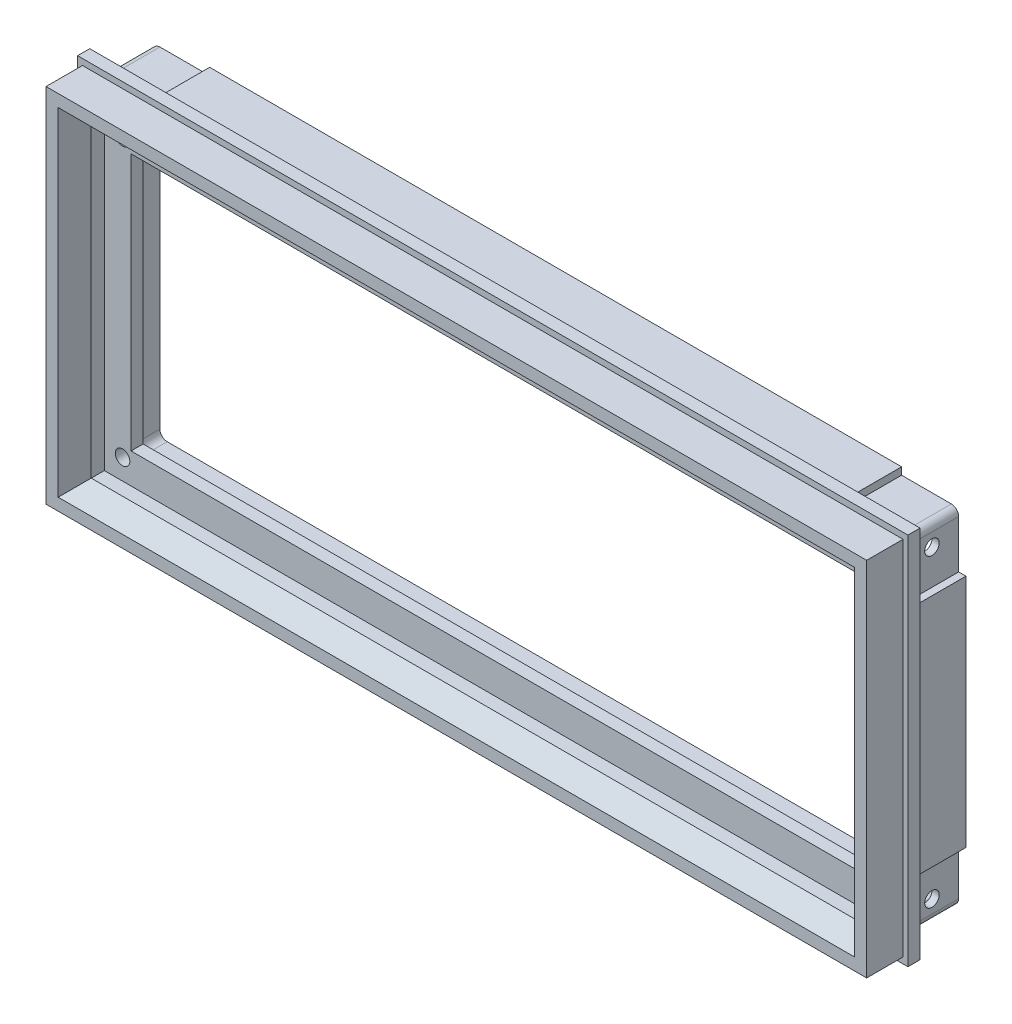
SolidWorks part; units mm, degrees
ref_plane "Plan de face" through (0, 0, 0) normal (0, 0, 1) x (1, 0, 0)
ref_plane "Plan de dessus" through (0, 0, 0) normal (0, 1, 0) x (1, 0, 0)
ref_plane "Plan de droite" through (0, 0, 0) normal (1, 0, 0) x (0, 0, -1)
sketch "Esquisse1" plane through (0, 0, 0) normal (0, 0, 1) x (1, 0, 0)
  line L1 (0, 0) -> (171, 0)
  line L2 (0, 0) -> (0, -77)
  line L3 (0, -77) -> (171, -77)
  line L4 (171, 0) -> (171, -77)
  line L5 (11, -12) -> (160, -12)
  line L6 (11, -12) -> (11, -65)
  line L7 (11, -65) -> (160, -65)
  line L8 (160, -12) -> (160, -65)
  line L9 (9.25, -10) -> (161.75, -10) construction
  line L10 (9.25, -10) -> (9.25, -67) construction
  line L11 (9.25, -67) -> (161.75, -67) construction
  line L12 (161.75, -10) -> (161.75, -67) construction
  circle A0 centre (9.25, -10) radius 1.5
  circle A1 centre (161.75, -10) radius 1.5
  circle A2 centre (161.75, -67) radius 1.5
  circle A3 centre (9.25, -67) radius 1.5
  point P9 (160, -38.5)
  point P10 (171, -38.5)
  point P11 (85.5, 0)
  point P12 (85.5, -12)
  point P21 (9.25, -38.5)
  point P22 (0, -38.5)
  point P23 (85.5, -67)
  point P24 (85.5, -77)
  dimension "D4" = 3
  dimension "D5" = 3
  dimension "D6" = 3
  dimension "D7" = 3
  dimension "D1" = 171
  dimension "D2" = 77
  dimension "D3" = 53
  dimension "D8" = 152.5
  dimension "D9" = 57
  dimension "D10" = 149
extrude "Boss.-Extru.1" add sketch "Esquisse1" along normal blind 2.5
sketch "Esquisse2" plane through (0, 0, 2.5) normal (0, 0, 1) x (1, 0, 0)
  line L0 (0, 0) -> (0, -77) construction
  line L1 (1, -1.25) -> (170, -1.25)
  line L2 (1, -1.25) -> (1, -75.75)
  line L3 (1, -75.75) -> (170, -75.75)
  line L4 (170, -1.25) -> (170, -75.75)
  line L5 (171, 0) -> (0, 0) construction
  line L7 (5.5, -5.75) -> (165.5, -5.75)
  line L8 (5.5, -5.75) -> (5.5, -71.25)
  line L9 (5.5, -71.25) -> (165.5, -71.25)
  line L10 (165.5, -5.75) -> (165.5, -71.25)
  point P6 (1, -38.5)
  point P7 (0, -38.5)
  point P10 (85.5, 0)
  point P11 (85.5, -1.25)
  dimension "D1" = 74.5
  dimension "D2" = 4.5
  dimension "D3" = 4.5
  dimension "D4" = 4.5
  dimension "D5" = 4.5
  dimension "D6" = 169
  dimension "D7" = 65.5
  dimension "D8" = 160
extrude "Boss.-Extru.2" add sketch "Esquisse2" along normal blind 7.5
chamfer "Chanfrein7" distance 2 angle 67.39 4 edges at (85.5, -71.25, 10) (165.5, -38.5, 10) (85.5, -5.75, 10) (5.5, -38.5, 10)
sketch "Esquisse4" plane through (0, 0, 0) normal (0, 0, -1) x (-1, 0, 0)
  line L0 (-171, 0) -> (0, 0) construction
  line L1 (-165.5, -4.425) -> (-5.5, -4.425)
  line L2 (-167, -5.925) -> (-167, -71.075)
  line L3 (-165.5, -72.575) -> (-5.5, -72.575)
  line L4 (-4, -5.925) -> (-4, -71.075)
  line L5 (-167, -2.925) -> (-4, -2.925)
  line L6 (-168.5, -4.425) -> (-168.5, -72.575)
  line L7 (-167, -74.075) -> (-4, -74.075)
  line L8 (-2.5, -4.425) -> (-2.5, -72.575)
  line L9 (-170, -1.425) -> (-1, -1.425) construction
  line L10 (-170, -1.425) -> (-170, -75.575) construction
  line L11 (-170, -75.575) -> (-1, -75.575) construction
  line L12 (-1, -1.425) -> (-1, -75.575) construction
  line L14 (-171, -77) -> (-171, 0) construction
  line L16 (-156.75, -75.575) -> (-14.25, -75.575)
  line L17 (-156.75, -75.575) -> (-156.75, -74.075)
  line L18 (-156.75, -74.075) -> (-14.25, -74.075)
  line L19 (-14.25, -75.575) -> (-14.25, -74.075)
  line L20 (-14.25, -2.925) -> (-156.75, -2.925)
  line L21 (-14.25, -2.925) -> (-14.25, -1.425)
  line L22 (-14.25, -1.425) -> (-156.75, -1.425)
  line L23 (-156.75, -2.925) -> (-156.75, -1.425)
  line L24 (-170, -14.3) -> (-168.5, -14.3)
  line L25 (-170, -14.3) -> (-170, -62.7)
  line L26 (-170, -62.7) -> (-168.5, -62.7)
  line L27 (-168.5, -14.3) -> (-168.5, -62.7)
  line L28 (-2.5, -62.7) -> (-1, -62.7)
  line L29 (-2.5, -62.7) -> (-2.5, -14.3)
  line L30 (-2.5, -14.3) -> (-1, -14.3)
  line L31 (-1, -62.7) -> (-1, -14.3)
  arc A0 (-4, -5.925) -> (-5.5, -4.425) centre (-5.5, -5.925) ccw
  arc A1 (-4, -2.925) -> (-2.5, -4.425) centre (-4, -4.425) cw
  arc A2 (-2.5, -72.575) -> (-4, -74.075) centre (-4, -72.575) cw
  arc A3 (-4, -71.075) -> (-5.5, -72.575) centre (-5.5, -71.075) cw
  arc A4 (-168.5, -72.575) -> (-167, -74.075) centre (-167, -72.575) ccw
  arc A5 (-167, -71.075) -> (-165.5, -72.575) centre (-165.5, -71.075) ccw
  arc A6 (-167, -2.925) -> (-168.5, -4.425) centre (-167, -4.425) ccw
  arc A7 (-167, -5.925) -> (-165.5, -4.425) centre (-165.5, -5.925) cw
  point P14 (-85.5, 0)
  point P15 (-85.5, -1.425)
  point P18 (-171, -38.5)
  point P19 (-170, -38.5)
  point P28 (-85.5, -2.925)
  point P29 (-85.5, -1.425)
  point P30 (-85.5, -75.575)
  point P31 (-85.5, -74.075)
  point P40 (-170, -38.5)
  point P41 (-168.5, -38.5)
  dimension "D14" = 1.5
  dimension "D1" = 1.5
  dimension "D2" = 1.5
  dimension "D3" = 1.5
  dimension "D4" = 1.5
  dimension "D5" = 3
  dimension "D6" = 3
  dimension "D7" = 3
  dimension "D8" = 3
  dimension "D9" = 74.15
  dimension "D10" = 169
  dimension "D11" = 142.5
  dimension "D12" = 142.5
  dimension "D13" = 48.4
extrude "Boss.-Extru.3" add sketch "Esquisse4" along normal blind 10.45 contours L5 A6 L6 A4 L7 A2 L8 A1 L2 A7 L1 A0 L4 A3 L3 A5 | L23 L5 L21 L22 | L25 L26 L6 L24 | L16 L19 L7 L17 | L28 L31 L30 L8
sketch "Esquisse5" plane through (168.5, 0, 0) normal (1, 0, 0) x (0, 0, -1)
  line L0 (4.95, -7.125) -> (4.95, -69.875) construction
  line L1 (10.45, -14.3) -> (10.45, -62.7) construction
  circle A0 centre (4.95, -7.125) radius 1.5
  circle A1 centre (4.95, -69.875) radius 1.5
  point P6 (10.45, -38.5)
  point P7 (4.95, -38.5)
  dimension "D2" = 3
  dimension "D3" = 3
  dimension "D1" = 5.5
  dimension "D4" = 62.75
extrude "Enlèv. mat.-Extru.1" cut sketch "Esquisse5" against normal through all
